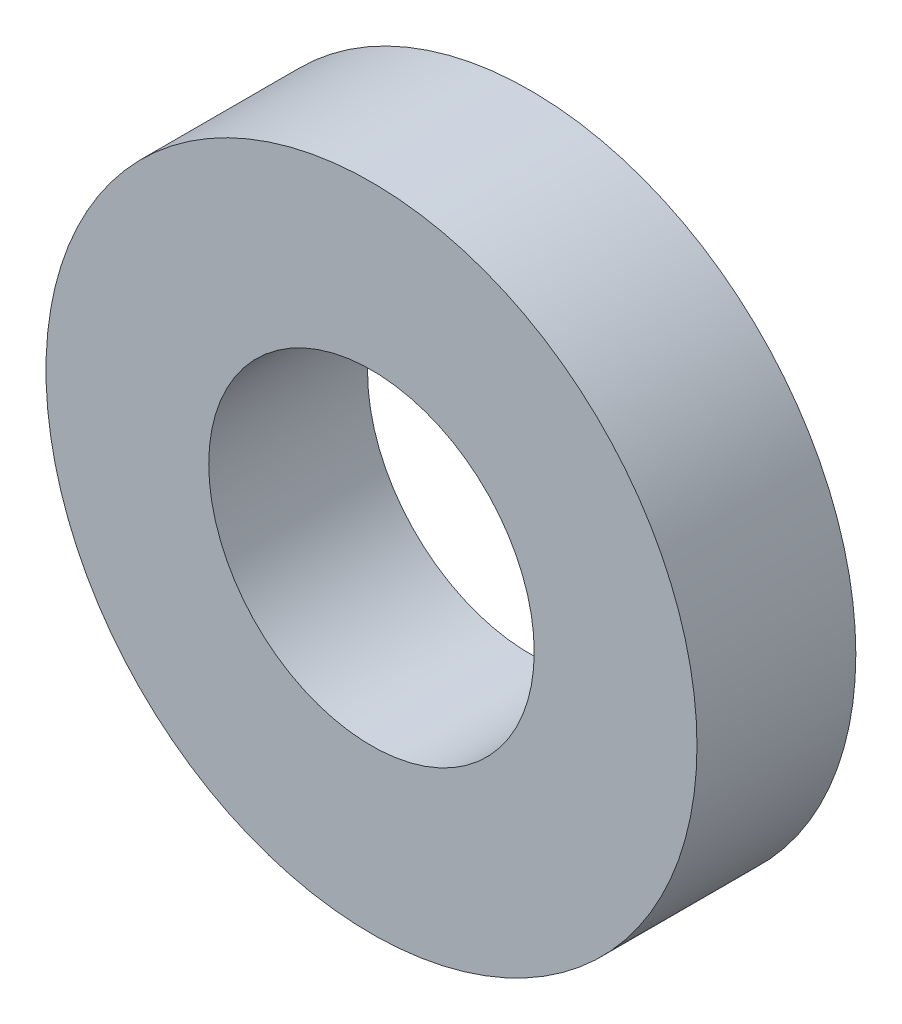
SolidWorks part; units mm, degrees
ref_plane "Front Plane" through (0, 0, 0) normal (0, 0, 1) x (1, 0, 0)
ref_plane "Top Plane" through (0, 0, 0) normal (0, 1, 0) x (1, 0, 0)
ref_plane "Right Plane" through (0, 0, 0) normal (1, 0, 0) x (0, 0, -1)
sketch "Sketch1" plane through (0, 0, 0) normal (0, 0, 1) x (1, 0, 0)
  circle A0 centre (0, 0) radius 6.35
  circle A1 centre (0, 0) radius 3.175
  dimension "D1" = 6.35
  dimension "D2" = 12.7
extrude "Boss-Extrude1" add sketch "Sketch1" along normal blind 3.0988
